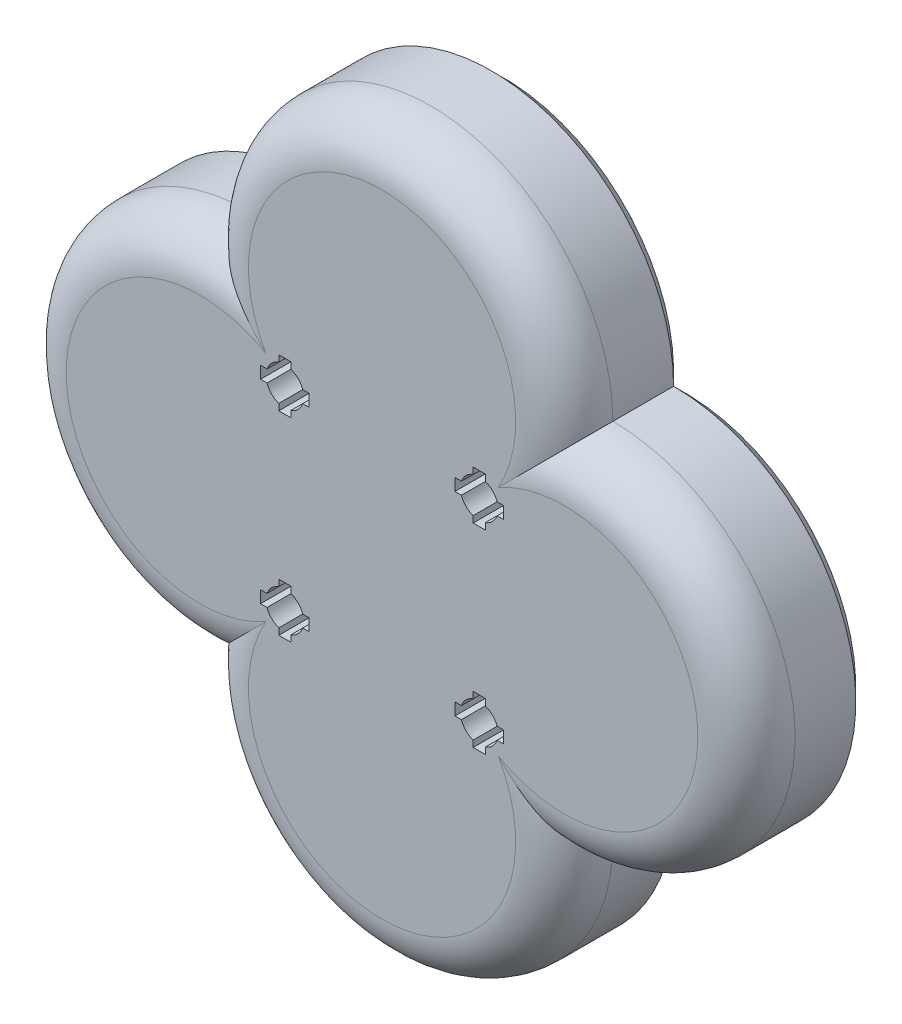
SolidWorks part; units mm, degrees
ref_plane "Front Plane" through (0, 0, 0) normal (0, 0, 1) x (1, 0, 0)
ref_plane "Top Plane" through (0, 0, 0) normal (0, 1, 0) x (1, 0, 0)
ref_plane "Right Plane" through (0, 0, 0) normal (1, 0, 0) x (0, 0, -1)
sketch "Sketch1" plane through (0, 0, 0) normal (0, 0, 1) x (1, 0, 0)
  line L0 (-8.6051, -8) -> (29.6268, -8) construction
  line L3 (8, 12.0814) -> (8, -10.8916) construction
  line L4 (-0.5, -2) -> (0.5, -2)
  line L5 (-0.5, -2) -> (-0.5, -1.4671)
  line L6 (-0.5, 2) -> (0.5, 2)
  line L7 (0.5, -2) -> (0.5, -1.4671)
  line L8 (-0.5, -2) -> (0.5, 2) construction
  line L9 (-0.5, 2) -> (0.5, -2) construction
  line L10 (-2, -0.5) -> (-1.4671, -0.5)
  line L11 (-2, -0.5) -> (-2, 0.5)
  line L12 (-2, 0.5) -> (-1.4671, 0.5)
  line L13 (2, -0.5) -> (2, 0.5)
  line L14 (-2, -0.5) -> (2, 0.5) construction
  line L15 (-2, 0.5) -> (2, -0.5) construction
  line L16 (0.5, 1.4671) -> (0.5, 2)
  line L17 (1.4671, 0.5) -> (2, 0.5)
  line L18 (-0.5, 1.4671) -> (-0.5, 2)
  line L19 (1.4671, -0.5) -> (2, -0.5)
  line L20 (18, -0.5) -> (18, 0.5)
  line L21 (18, 0.5) -> (17.4671, 0.5)
  line L22 (16.5, 1.4671) -> (16.5, 2)
  line L23 (16.5, 2) -> (15.5, 2)
  line L24 (15.5, 1.4671) -> (15.5, 2)
  line L25 (14.5329, 0.5) -> (14, 0.5)
  line L26 (14, -0.5) -> (14, 0.5)
  line L27 (14.5329, -0.5) -> (14, -0.5)
  line L28 (15.5, -2) -> (15.5, -1.4671)
  line L29 (16.5, -2) -> (15.5, -2)
  line L30 (16.5, -2) -> (16.5, -1.4671)
  line L31 (18, -0.5) -> (17.4671, -0.5)
  line L32 (18, -15.5) -> (17.4671, -15.5)
  line L33 (16.5, -14) -> (16.5, -14.5329)
  line L34 (16.5, -14) -> (15.5, -14)
  line L35 (15.5, -14) -> (15.5, -14.5329)
  line L36 (14.5329, -15.5) -> (14, -15.5)
  line L37 (14, -15.5) -> (14, -16.5)
  line L38 (14.5329, -16.5) -> (14, -16.5)
  line L39 (15.5, -17.4671) -> (15.5, -18)
  line L40 (16.5, -18) -> (15.5, -18)
  line L41 (16.5, -17.4671) -> (16.5, -18)
  line L42 (18, -16.5) -> (17.4671, -16.5)
  line L43 (18, -15.5) -> (18, -16.5)
  line L44 (-2, -15.5) -> (-2, -16.5)
  line L45 (-2, -16.5) -> (-1.4671, -16.5)
  line L46 (-0.5, -17.4671) -> (-0.5, -18)
  line L47 (-0.5, -18) -> (0.5, -18)
  line L48 (0.5, -17.4671) -> (0.5, -18)
  line L49 (1.4671, -16.5) -> (2, -16.5)
  line L50 (2, -15.5) -> (2, -16.5)
  line L51 (1.4671, -15.5) -> (2, -15.5)
  line L52 (0.5, -14) -> (0.5, -14.5329)
  line L53 (-0.5, -14) -> (0.5, -14)
  line L54 (-0.5, -14) -> (-0.5, -14.5329)
  line L55 (-2, -15.5) -> (-1.4671, -15.5)
  line L57 (-7, -23) -> (23, -23)
  line L58 (-7, -23) -> (-7, 7)
  line L59 (-7, 7) -> (23, 7)
  line L60 (23, -23) -> (23, 7)
  line L61 (-7, -23) -> (23, 7) construction
  line L62 (-7, 7) -> (23, -23) construction
  arc A0 (-0.5, 1.4671) -> (-1.4671, 0.5) centre (0, 0) ccw
  arc A3 (-1.4671, -0.5) -> (-0.5, -1.4671) centre (0, 0) ccw
  arc A4 (1.4671, 0.5) -> (0.5, 1.4671) centre (0, 0) ccw
  arc A5 (0.5, -1.4671) -> (1.4671, -0.5) centre (0, 0) ccw
  arc A6 (16.5, 1.4671) -> (17.4671, 0.5) centre (16, 0) cw
  arc A7 (14.5329, 0.5) -> (15.5, 1.4671) centre (16, 0) cw
  arc A8 (15.5, -1.4671) -> (14.5329, -0.5) centre (16, 0) cw
  arc A9 (17.4671, -0.5) -> (16.5, -1.4671) centre (16, 0) cw
  arc A10 (17.4671, -15.5) -> (16.5, -14.5329) centre (16, -16) ccw
  arc A11 (15.5, -14.5329) -> (14.5329, -15.5) centre (16, -16) ccw
  arc A12 (14.5329, -16.5) -> (15.5, -17.4671) centre (16, -16) ccw
  arc A13 (16.5, -17.4671) -> (17.4671, -16.5) centre (16, -16) ccw
  arc A14 (-0.5, -17.4671) -> (-1.4671, -16.5) centre (0, -16) cw
  arc A15 (1.4671, -16.5) -> (0.5, -17.4671) centre (0, -16) cw
  arc A16 (0.5, -14.5329) -> (1.4671, -15.5) centre (0, -16) cw
  arc A17 (-1.4671, -15.5) -> (-0.5, -14.5329) centre (0, -16) cw
  arc A18 (-7, 7) -> (23, 7) centre (8, 7) cw
  arc A19 (23, 7) -> (23, -23) centre (23, -8) cw
  arc A20 (23, -23) -> (-7, -23) centre (8, -23) cw
  arc A21 (-7, 7) -> (-7, -23) centre (-7, -8) ccw
  point P73 (8, -8)
  dimension "D1" = 3.1
  dimension "D2" = 8
  dimension "D3" = 8
  dimension "D4" = 1
  dimension "D5" = 30
  dimension "D6" = 1
  dimension "D7" = 4
  dimension "D8" = 4
  dimension "D9" = 30
extrude "Boss-Extrude1" add sketch "Sketch1" along normal blind 10 contours A18 L59 | L58 A21 | L57 L60 L59 L58 A13 L41 L40 L39 A12 L38 L37 L36 A11 L35 L34 L33 A10 L32 L43 L42 A5 L7 L4 L5 A3 L10 L11 L12 A0 L18 L6 L16 A4 L17 L13 L19 L31 A9 L30 L29 L28 A8 L27 L26 L25 A7 L24 L23 | A19 L60 | A20 L57
fillet "Fillet1" radius 4 4 edges at (8, -38, 10) (38, -8, 10) (8, 22, 10) (-22, -8, 10)
chamfer "Chamfer1" distance 1 angle 45 4 edges at (8, 22, 0) (38, -8, 0) (8, -38, 0) (-22, -8, 0)
